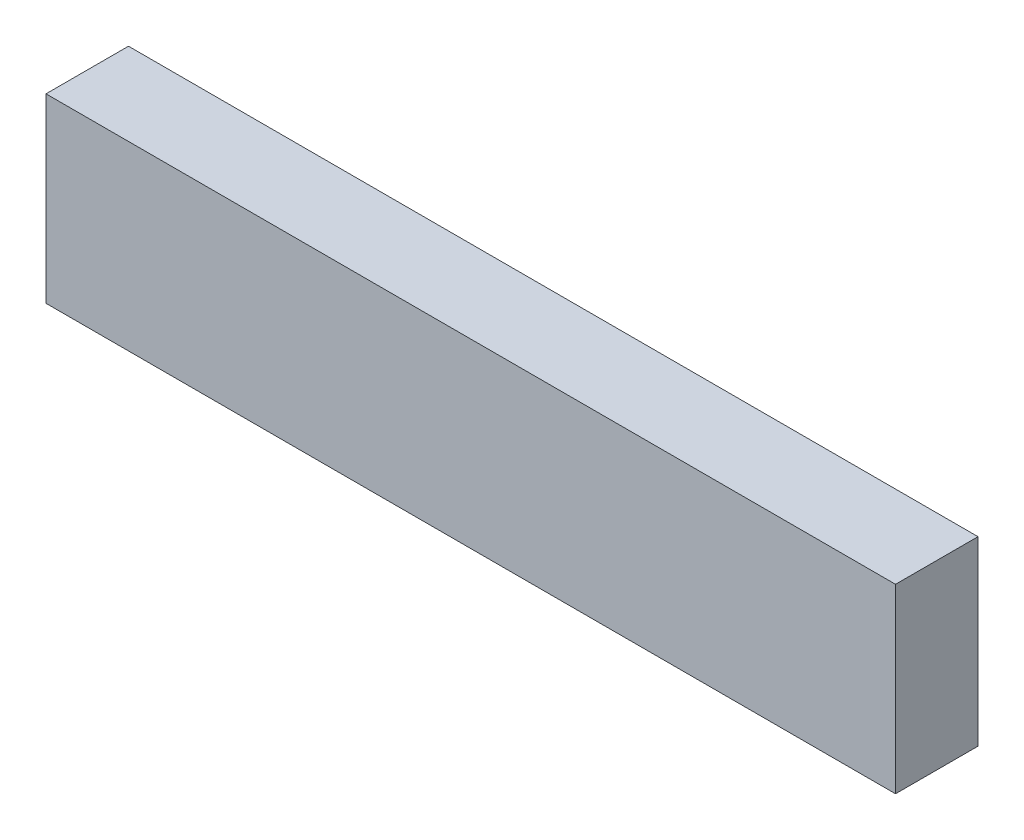
SolidWorks part; units mm, degrees
ref_plane "Спереди" through (0, 0, 0) normal (0, 0, 1) x (1, 0, 0)
ref_plane "Сверху" through (0, 0, 0) normal (0, 1, 0) x (1, 0, 0)
ref_plane "Справа" through (0, 0, 0) normal (1, 0, 0) x (0, 0, -1)
sketch "Эскиз1" plane through (0, 0, 0) normal (0, 1, 0) x (1, 0, 0)
  line L1 (-25.75, -2.5) -> (25.75, -2.5)
  line L2 (-25.75, -2.5) -> (-25.75, 2.5)
  line L3 (-25.75, 2.5) -> (25.75, 2.5)
  line L4 (25.75, -2.5) -> (25.75, 2.5)
  line L5 (-25.75, -2.5) -> (25.75, 2.5) construction
  line L6 (-25.75, 2.5) -> (25.75, -2.5) construction
  point P0 (0, 0)
  dimension "D1" = 5
  dimension "D2" = 51.5
extrude "Бобышка-Вытянуть1" add sketch "Эскиз1" along normal blind 11
